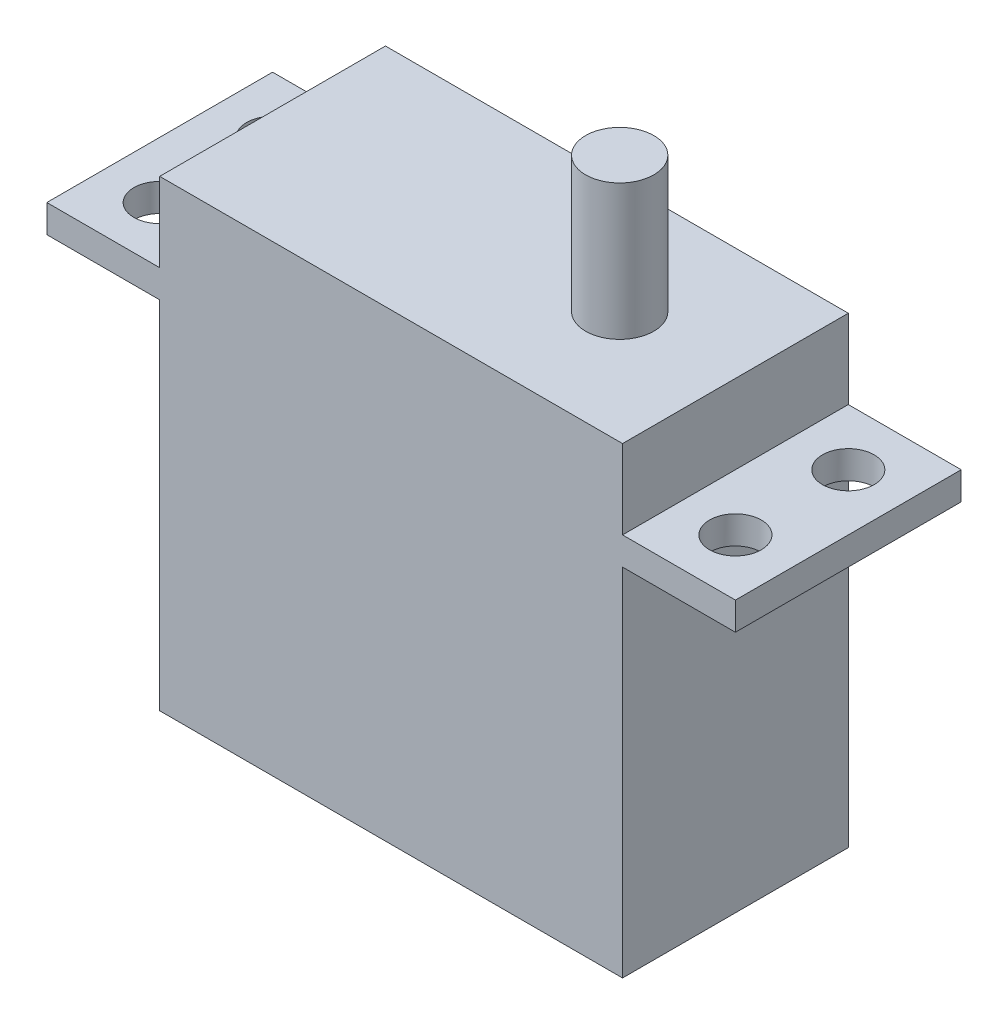
SolidWorks part; units mm, degrees
ref_plane "Front Plane" through (0, 0, 0) normal (0, 0, 1) x (1, 0, 0)
ref_plane "Top Plane" through (0, 0, 0) normal (0, 1, 0) x (1, 0, 0)
ref_plane "Right Plane" through (0, 0, 0) normal (1, 0, 0) x (0, 0, -1)
sketch "Sketch1" plane through (0, 0, 0) normal (0, 1, 0) x (1, 0, 0)
  line L1 (-10.25, 10) -> (10.25, 10)
  line L2 (-10.25, 10) -> (-10.25, -10)
  line L3 (-10.25, -10) -> (10.25, -10)
  line L4 (10.25, 10) -> (10.25, -10)
  line L5 (-10.25, 10) -> (10.25, -10) construction
  line L6 (-10.25, -10) -> (10.25, 10) construction
  point P0 (0, 0)
extrude "Boss-Extrude1" add sketch "Sketch1" along normal blind 41
sketch "Sketch3" plane through (-10.25, 0, 0) normal (-1, 0, 0) x (0, 0, 1)
  line L0 (10, 41) -> (10, 0) construction
  line L1 (10, 33.9931) -> (-10, 33.9931)
  line L2 (10, 33.9931) -> (10, 31.5252)
  line L3 (10, 31.5252) -> (-10, 31.5252)
  line L4 (-10, 33.9931) -> (-10, 31.5252)
  line L5 (-10, 41) -> (-10, 0) construction
extrude "Boss-Extrude2" add sketch "Sketch3" along normal blind 10
sketch "Sketch4" plane through (0, 33.9931, 0) normal (0, 1, 0) x (1, 0, 0)
  line L1 (-20.25, 10) -> (-10.25, 10) construction
  line L2 (-20.25, -10) -> (-10.25, -10) construction
  line L3 (-15.25, -10) -> (-15.25, 0) construction
  line L4 (-15.25, 0) -> (-15.25, 10) construction
  circle A0 centre (-15.25, 5) radius 2.2903
  circle A1 centre (-15.25, -5) radius 2.2903
  dimension "D1" = 2
extrude "Cut-Extrude9" cut sketch "Sketch4" against normal blind 10
mirror "Mirror1" about plane through (10.25, 41, -10) normal (-1, 0, 0) of "Boss-Extrude1", "Cut-Extrude9", "Boss-Extrude2"
sketch "Sketch5" plane through (0, 41, 0) normal (0, 1, 0) x (1, 0, 0)
  line L0 (10.25, 10) -> (10.25, -10) construction
  line L1 (30.75, 10) -> (-10.25, 10) construction
  line L2 (-10.25, -10) -> (30.75, -10) construction
  line L3 (10.25, -10) -> (10.25, 0) construction
  line L4 (10.25, 0) -> (30.75, 10) construction
  line L5 (30.75, 10) -> (10.25, -10) construction
  line L6 (10.25, -10) -> (10.25, 10) construction
  line L7 (10.25, 10) -> (30.75, -10) construction
  line L8 (30.75, -10) -> (30.75, 10) construction
  line L9 (30.75, 10) -> (30.75, -10) construction
  circle A0 centre (20.5, 0) radius 3.0187
extrude "Boss-Extrude3" add sketch "Sketch5" along normal blind 12
